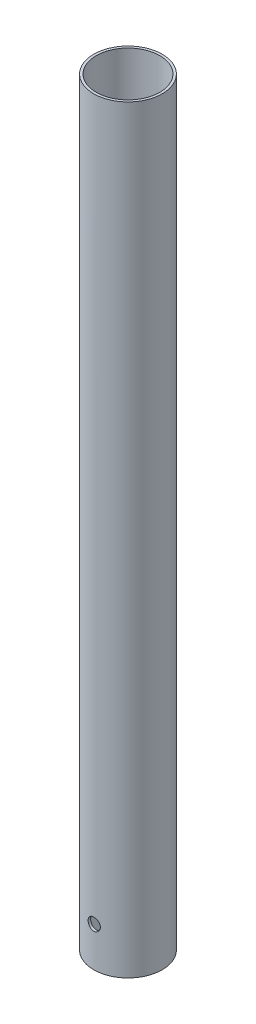
SolidWorks part; units mm, degrees
material "Hexcel AS4C (3000 丝)"
ref_plane "前视基准面" through (0, 0, 0) normal (0, 0, 1) x (1, 0, 0)
ref_plane "上视基准面" through (0, 0, 0) normal (0, 1, 0) x (1, 0, 0)
ref_plane "右视基准面" through (0, 0, 0) normal (1, 0, 0) x (0, 0, -1)
sketch "草图1" plane through (0, 0, 0) normal (0, 1, 0) x (1, 0, 0)
  circle A0 centre (0, 0) radius 14
  circle A1 centre (0, 0) radius 13
  dimension "D1" = 28
  dimension "D2" = 26
extrude "凸台-拉伸1" add sketch "草图1" along normal blind 310
sketch "草图2" plane through (0, 0, 0) normal (0, 0, 1) x (1, 0, 0)
  circle A0 centre (0, 16.17) radius 2.5
  dimension "D1" = 5
  dimension "D2" = 16.17
extrude "切除-拉伸1" cut sketch "草图2" against normal through all both and the other way through all
